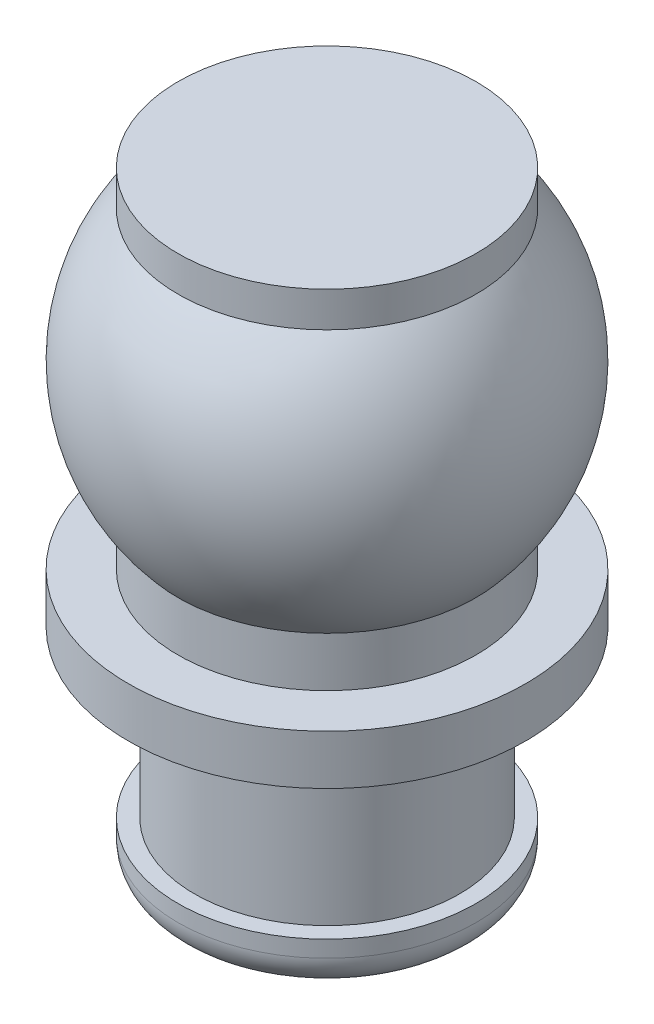
SolidWorks part; units mm, degrees
ref_plane "Plan de face" through (0, 0, 0) normal (0, 0, 1) x (1, 0, 0)
ref_plane "Plan de dessus" through (0, 0, 0) normal (0, 1, 0) x (1, 0, 0)
ref_plane "Plan de droite" through (0, 0, 0) normal (1, 0, 0) x (0, 0, -1)
sketch "Esquisse1" plane through (0, 0, 0) normal (0, 0, 1) x (1, 0, 0)
  line L0 (0, 0) -> (0, 68.7932) construction
  line L1 (-4.5, 39.2896) -> (-4.5, 37.7896)
  line L2 (-4.5, 37.7896) -> (-6, 37.7896)
  line L3 (-6, 37.7896) -> (-6, 36.2896)
  line L4 (-6, 36.2896) -> (-4, 36.2896)
  line L5 (-4, 36.2896) -> (-4, 31.2896)
  line L6 (-4, 31.2896) -> (-4.5, 31.2896)
  line L7 (-4.5, 31.2896) -> (-4.5, 29.7896)
  line L8 (-4.5, 29.7896) -> (0, 29.7896)
  line L9 (0, 29.7896) -> (0, 48.2896)
  line L10 (0, 48.2896) -> (-4.5, 48.2896)
  line L11 (-4.5, 48.2896) -> (-4.5, 47.2268)
  arc A0 (-4.5, 47.2268) -> (-4.5, 39.2896) centre (0, 43.2582) ccw
  dimension "D1" = 12
  dimension "D2" = 4.5
  dimension "D3" = 4.5
  dimension "D4" = 4
  dimension "D5" = 4.5
  dimension "D6" = 6
  dimension "D7" = 1.5
  dimension "D8" = 5
  dimension "D9" = 1.5
  dimension "D10" = 10.5
  dimension "D11" = 1.5
revolve "Révolution1" add sketch "Esquisse1" angle 360 about L0
fillet "Congé1" radius 1 1 edges at (0, 29.7896, -4.5)
